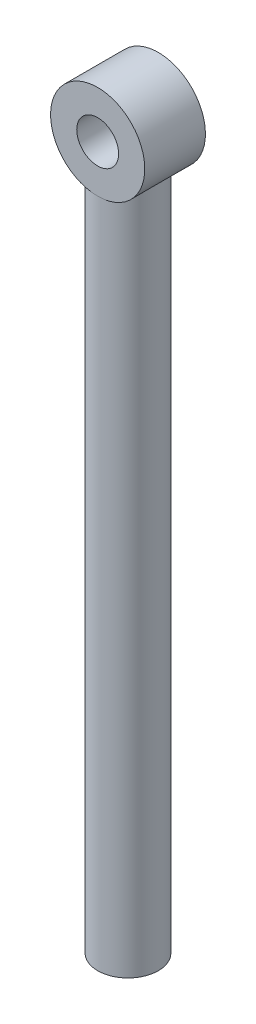
SolidWorks part; units mm, degrees
ref_plane "前基準面" through (0, 0, 0) normal (0, 0, 1) x (1, 0, 0)
ref_plane "上基準面" through (0, 0, 0) normal (0, 1, 0) x (1, 0, 0)
ref_plane "右基準面" through (0, 0, 0) normal (1, 0, 0) x (0, 0, -1)
sketch "草圖1" plane through (0, 0, 0) normal (0, 1, 0) x (1, 0, 0)
  circle A0 centre (0, 0) radius 5.795
  dimension "D1" = 11.59
extrude "填料-伸長1" add sketch "草圖1" along normal blind 132.19
sketch "草圖3" plane through (0, 0, 0) normal (0, 0, 1) x (1, 0, 0)
  line L0 (0, 132.19) -> (0, 137.19) construction
  line L1 (5.795, 132.19) -> (-5.795, 132.19) construction
  circle A0 centre (0, 137.19) radius 4
  dimension "D2" = 8
  dimension "D3" = 8
  dimension "D1" = 5
extrude "伸長-薄件1" add sketch "草圖3" along normal blind 6.19 and the other way blind 6 thin
sketch "草圖7" plane through (0, 0, 0) normal (0, -1, 0) x (1, 0, 0)
  line L0 (0, 5.795) -> (-10.2177, 5.795)
  line L1 (-10.2177, 5.795) -> (-10.2177, 6.2999)
  line L2 (-10.2177, 6.2999) -> (9.3313, 6.2999)
  line L3 (9.3313, 6.2999) -> (9.3313, 5.795)
  line L4 (9.3313, 5.795) -> (0, 5.795)
  circle A0 centre (0, 0) radius 5.795 construction
  circle A1 centre (0, 0) radius 5.795 construction
extrude "除料-伸長1" cut sketch "草圖7" against normal blind 169.19
sketch "草圖8" plane through (0, 0, 0) normal (0, -1, 0) x (1, 0, 0)
  line L0 (0, -5.795) -> (-9.7865, -5.795)
  line L1 (-9.7865, -5.795) -> (-9.7865, -6.6667)
  line L2 (-9.7865, -6.6667) -> (9.3073, -6.6667)
  line L3 (9.3073, -6.6667) -> (9.3073, -5.795)
  line L4 (9.3073, -5.795) -> (0, -5.795)
  circle A0 centre (0, 0) radius 5.795 construction
  circle A1 centre (0, 0) radius 5.795 construction
extrude "除料-伸長2" cut sketch "草圖8" against normal through all
